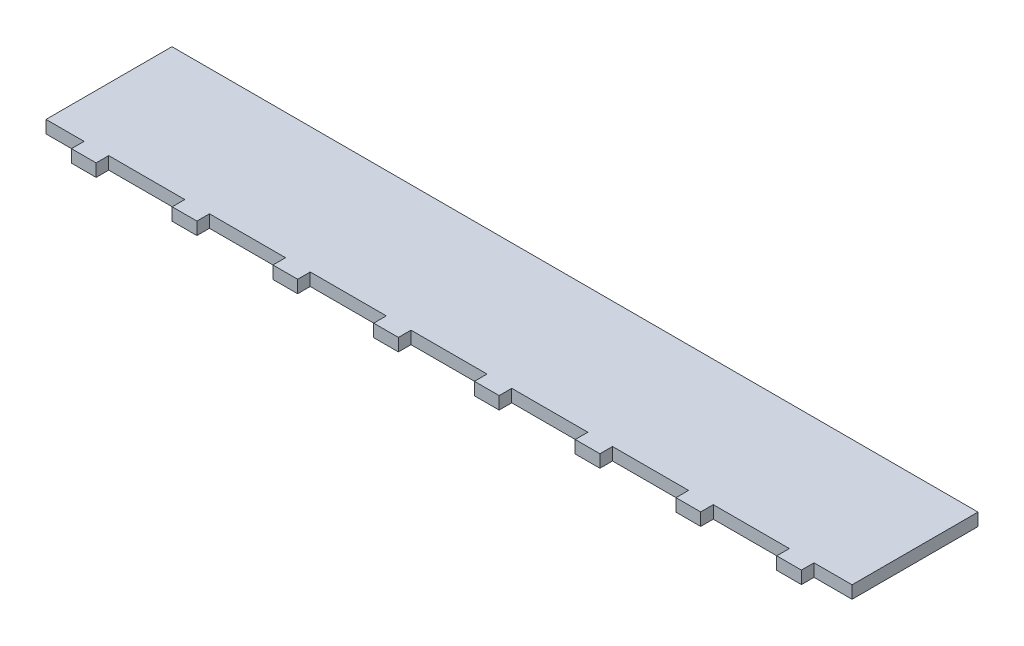
SolidWorks part; units mm, degrees
ref_plane "Front Plane" through (0, 0, 0) normal (0, 0, 1) x (1, 0, 0)
ref_plane "Top Plane" through (0, 0, 0) normal (0, 1, 0) x (1, 0, 0)
ref_plane "Right Plane" through (0, 0, 0) normal (1, 0, 0) x (0, 0, -1)
sketch "Sketch1" plane through (0, 0, 0) normal (0, 1, 0) x (1, 0, 0)
  line L1 (-101.6, 15.875) -> (101.6, 15.875)
  line L2 (-101.6, 15.875) -> (-101.6, -15.875)
  line L3 (-101.6, -15.875) -> (101.6, -15.875)
  line L4 (101.6, 15.875) -> (101.6, -15.875)
  line L5 (-101.6, 15.875) -> (101.6, -15.875) construction
  line L6 (-101.6, -15.875) -> (101.6, 15.875) construction
  point P0 (0, 0)
  dimension "D1" = 203.2
  dimension "D2" = 31.75
extrude "Boss-Extrude1" add sketch "Sketch1" along normal blind 3.175
sketch "Sketch2" plane through (0, 0, 15.875) normal (0, 0, 1) x (1, 0, 0)
  line L0 (-101.6, 3.175) -> (101.6, 3.175) construction
  line L1 (85.7885, 3.175) -> (92.0115, 3.175)
  line L2 (85.7885, 3.175) -> (85.7885, 0)
  line L3 (85.7885, 0) -> (92.0115, 0)
  line L4 (92.0115, 3.175) -> (92.0115, 0)
  line L5 (-101.6, 0) -> (101.6, 0) construction
  line L7 (101.6, 3.175) -> (101.6, 0) construction
  point P10 (101.6, 1.5875)
  dimension "D1" = 9.5885
  dimension "D2" = 6.223
extrude "Boss-Extrude2" add sketch "Sketch2" along normal blind 3.175
pattern_linear "LPattern1" count 8 spacing 25.4 along (-1, 0, 0) of "Boss-Extrude2"
